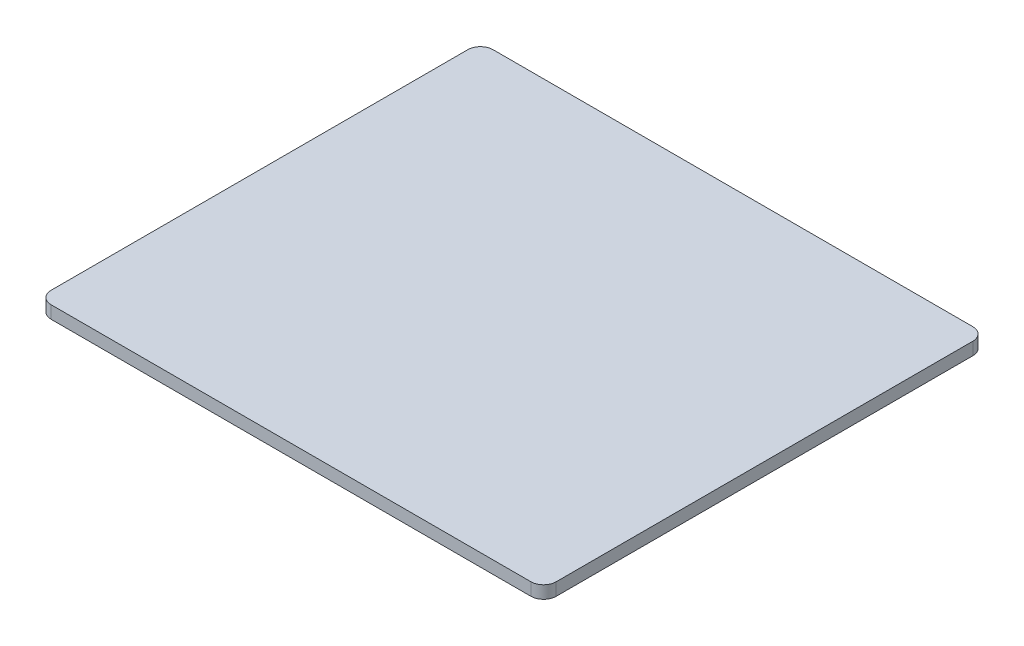
SolidWorks part; units mm, degrees
ref_plane "Front Plane" through (0, 0, 0) normal (0, 0, 1) x (1, 0, 0)
ref_plane "Top Plane" through (0, 0, 0) normal (0, 1, 0) x (1, 0, 0)
ref_plane "Right Plane" through (0, 0, 0) normal (1, 0, 0) x (0, 0, -1)
sketch "Sketch1" plane through (0, 0, 0) normal (0, 1, 0) x (1, 0, 0)
  line L1 (-200, 175) -> (200, 175)
  line L2 (-200, 175) -> (-200, -175)
  line L3 (-200, -175) -> (200, -175)
  line L4 (200, 175) -> (200, -175)
  line L5 (-200, 175) -> (200, -175) construction
  line L6 (-200, -175) -> (200, 175) construction
  point P0 (0, 0)
  dimension "D1" = 400
  dimension "D2" = 350
extrude "Boss-Extrude1" add sketch "Sketch1" along normal blind 10
hole_wizard "CBORE for M8 Pan Head Machine Screw1" positions "Sketch3" profile "Sketch2" counterbore size "M8" standard "ANSI Metric"
sketch "Sketch3" plane through (0, 0, 0) normal (0, -1, 0) x (-1, 0, 0)
  line L0 (200, 200) -> (200, -200) construction
  line L1 (-200, 200) -> (200, 200) construction
  line L2 (200, -200) -> (-200, -200) construction
  line L3 (-200, -200) -> (-200, 200) construction
  point P0 (185, -185)
  point P2 (-185, -185)
  point P4 (-140, 185)
  point P6 (185, 185)
  dimension "D1" = 15
  dimension "D2" = 15
  dimension "D3" = 15
  dimension "D4" = 15
  dimension "D5" = 15
  dimension "D6" = 15
  dimension "D7" = 60
  dimension "D8" = 15
sketch "Sketch2" plane through (-185, 0, 185) normal (1, 0, 0) x (0, 0, -1)
  line L0 (0, 0) -> (0, 10)
  line L1 (0, 10) -> (4.2, 10)
  line L3 (4.2, 10) -> (4.2, 6)
  line L4 (4.2, 6) -> (9, 6)
  line L5 (9, 6) -> (9, 0)
  line L7 (9, 0) -> (0, 0)
  line L11 (0, -6.35) -> (0, 107.95) construction
  dimension "Thru Hole Dia." = 8.4
  dimension "Thru Hole Depth" = 10
  dimension "C'Bore Dia." = 18
  dimension "C'Bore Depth" = 6
fillet "Fillet1" radius 10 4 edges at (-200, 5, -175) (200, 5, -175) (200, 5, 175) (-200, 5, 175)
